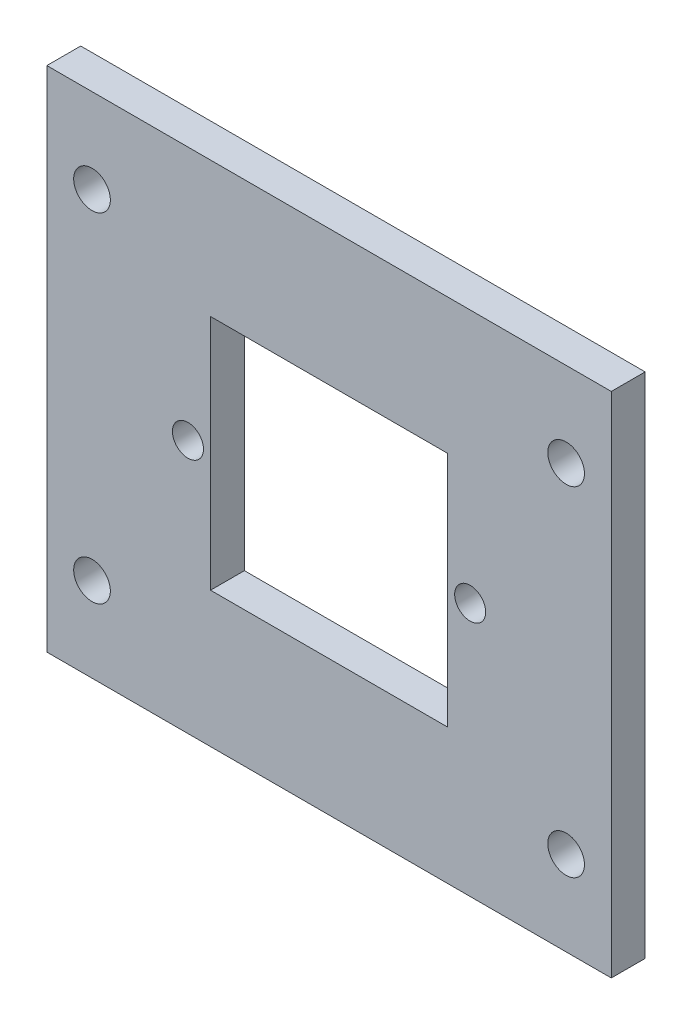
SolidWorks part; units mm, degrees
ref_plane "Front Plane" through (0, 0, 0) normal (0, 0, 1) x (1, 0, 0)
ref_plane "Top Plane" through (0, 0, 0) normal (0, 1, 0) x (1, 0, 0)
ref_plane "Right Plane" through (0, 0, 0) normal (1, 0, 0) x (0, 0, -1)
sketch "Sketch1" plane through (0, 0, 0) normal (0, 0, 1) x (1, 0, 0)
  line L1 (50, 45) -> (-50, 45)
  line L2 (50, 45) -> (50, -45)
  line L3 (50, -45) -> (-50, -45)
  line L4 (-50, 45) -> (-50, -45)
  line L5 (50, 45) -> (-50, -45) construction
  line L6 (50, -45) -> (-50, 45) construction
  point P0 (0, 0)
  dimension "D1" = 90
  dimension "D2" = 100
extrude "Boss-Extrude1" add sketch "Sketch1" along normal blind 6
sketch "Sketch2" plane through (0, 0, 6) normal (0, 0, 1) x (1, 0, 0)
  line L0 (0, 27.6425) -> (0, -26.2546) construction
  line L1 (50, 45) -> (-50, 45) construction
  line L2 (-36.8953, 0) -> (24.8667, 0) construction
  line L3 (-50, 45) -> (-50, -45) construction
  circle A0 centre (-25, 0) radius 2.75
  circle A1 centre (-42, 30) radius 3.25
  circle A2 centre (-42, -30) radius 3.25
  circle A3 centre (42, -30) radius 3.25
  circle A4 centre (25, 0) radius 2.75
  circle A5 centre (42, 30) radius 3.25
  dimension "D1" = 5.5
  dimension "D2" = 6.5
  dimension "D3" = 15
  dimension "D4" = 25
  dimension "D5" = 8
extrude "Cut-Extrude1" cut sketch "Sketch2" against normal through all
sketch "Sketch3" plane through (0, 0, 6) normal (0, 0, 1) x (1, 0, 0)
  line L1 (21, 21) -> (-21, 21)
  line L2 (21, 21) -> (21, -21)
  line L3 (21, -21) -> (-21, -21)
  line L4 (-21, 21) -> (-21, -21)
  line L5 (21, 21) -> (-21, -21) construction
  line L6 (21, -21) -> (-21, 21) construction
  point P0 (0, 0)
  dimension "D1" = 42
  dimension "D2" = 42
extrude "Cut-Extrude2" cut sketch "Sketch3" against normal blind 10
